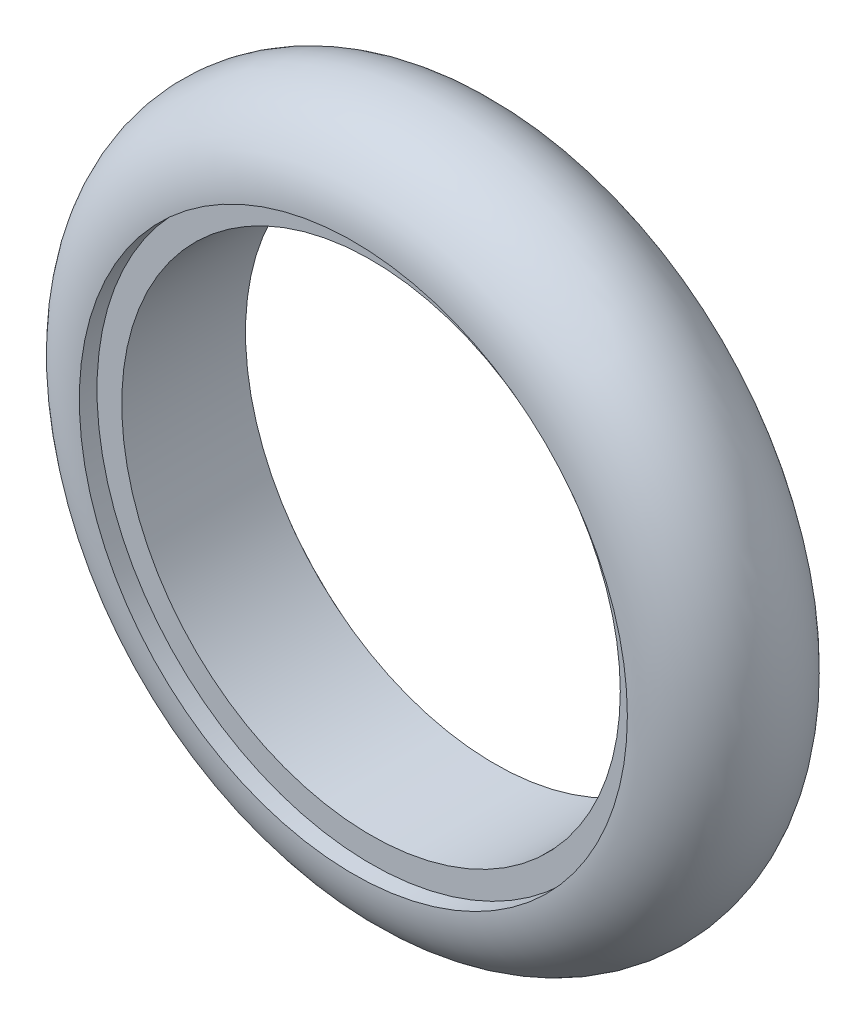
SolidWorks part; units mm, degrees
ref_plane "Front Plane" through (0, 0, 0) normal (0, 0, 1) x (1, 0, 0)
ref_plane "Top Plane" through (0, 0, 0) normal (0, 1, 0) x (1, 0, 0)
ref_plane "Right Plane" through (0, 0, 0) normal (1, 0, 0) x (0, 0, -1)
sketch "Sketch2" plane through (0, 0, 0) normal (1, 0, 0) x (0, 0, -1)
  line L0 (-22.5, 77.5) -> (-17.5, 77.5)
  line L1 (0, 0) -> (121683.6747, 0) construction
  line L2 (-17.5, 77.5) -> (-17.5, 70.5)
  line L3 (-17.5, 70.5) -> (17.5, 70.5)
  line L4 (17.5, 70.5) -> (17.5, 77.5)
  line L5 (17.5, 77.5) -> (22.5, 77.5)
  line L6 (-991.4472, 100.5) -> (49008.5528, 100.5) construction
  arc A0 (-22.5, 77.5) -> (22.5, 77.5) centre (0, 77.5) cw
  point P9 (0, 70.5)
  dimension "D1" = 155
  dimension "D2" = 155
  dimension "D3" = 45
  dimension "D4" = 35
  dimension "D5" = 7
  dimension "D6" = 23
  dimension "D7" = 141
revolve "Revolve1" add sketch "Sketch2" angle 360 about L1
